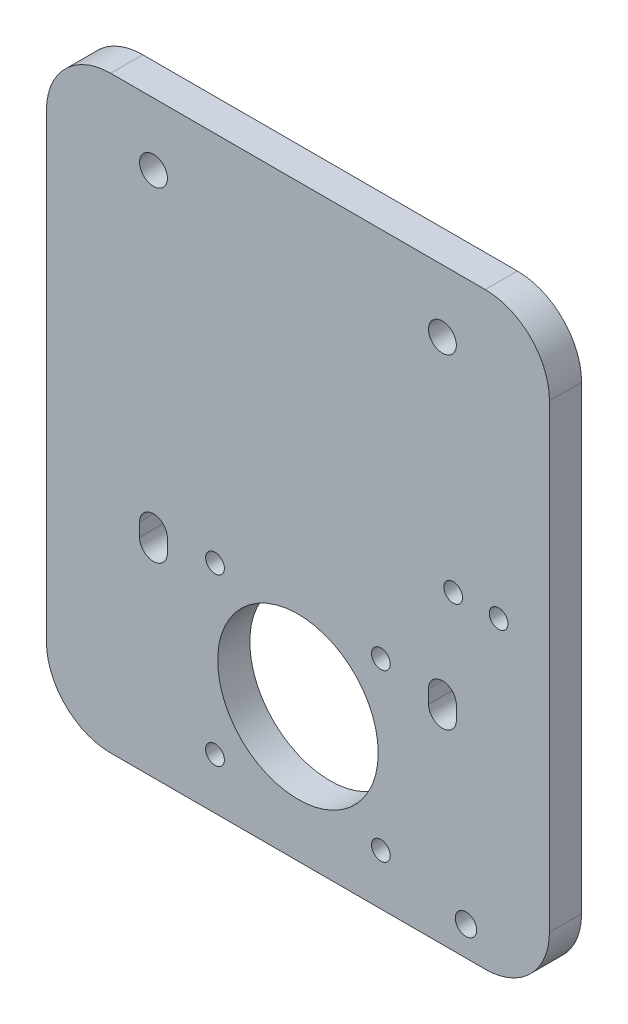
SolidWorks part; units mm, degrees
material "Acrylic (Medium-high impact)"
ref_plane "Спереди" through (0, 0, 0) normal (0, 0, 1) x (1, 0, 0)
ref_plane "Сверху" through (0, 0, 0) normal (0, 1, 0) x (1, 0, 0)
ref_plane "Справа" through (0, 0, 0) normal (1, 0, 0) x (0, 0, -1)
sketch "Model" plane through (0, 0, 0) normal (0, 0, 1) x (1, 0, 0)
  line L4 (-22.7195, 98.3) -> (-31.6357, 98.3) construction
  line L5 (-27, 102.2644) -> (-27, 93.0751) construction
  line L24 (-27, 44.8397) -> (-27, 32.6753) construction
  line L25 (-29.6, 40.1) -> (-29.6, 37.6)
  line L26 (-24.4, 37.6) -> (-24.4, 40.1)
  line L27 (-24.4, 40.1) -> (-24.4, 37.6)
  line L28 (-29.6, 37.6) -> (-29.6, 40.1)
  line L156 (-18.8648, 25) -> (20.0371, 25) construction
  line L157 (13.2088, 9.5) -> (17.9881, 9.5) construction
  line L158 (15.5, 11.4003) -> (15.5, 7.7373) construction
  line L159 (27, 44.8397) -> (27, 32.6753) construction
  line L160 (47, 98) -> (47, 12)
  line L165 (27, 102.2644) -> (27, 93.0751) construction
  line L166 (22.7195, 98.3) -> (31.6357, 98.3) construction
  line L167 (35, 0) -> (-35, 0)
  line L171 (15.5, 38.5997) -> (15.5, 42.2627) construction
  line L172 (13.2088, 40.5) -> (17.9881, 40.5) construction
  line L173 (-13.2088, 40.5) -> (-17.9881, 40.5) construction
  line L174 (-47, 12) -> (-47, 98)
  line L175 (-15.5, 38.5997) -> (-15.5, 42.2627) construction
  line L176 (-15.5, 11.4003) -> (-15.5, 7.7373) construction
  line L177 (-13.2088, 9.5) -> (-17.9881, 9.5) construction
  line L181 (-35, 110) -> (35, 110)
  line L955 (29.6, 37.6) -> (29.6, 40.1)
  line L968 (24.4, 40.1) -> (24.4, 37.6)
  line L1360 (24.4, 37.6) -> (24.4, 40.1)
  line L1373 (29.6, 40.1) -> (29.6, 37.6)
  line L1604 (0, -6.1891) -> (0, 116.9068) construction
  arc A0 (35, 110) -> (47, 98) centre (35, 98) cw
  arc A1 (47, 12) -> (35, 0) centre (35, 12) cw
  arc A2 (-47, 12) -> (-35, 0) centre (-35, 12) ccw
  arc A3 (-47, 98) -> (-35, 110) centre (-35, 98) cw
  circle A4 centre (15.5, 9.5) radius 1.75
  circle A5 centre (15.5, 40.5) radius 1.75
  circle A6 centre (-15.5, 40.5) radius 1.75
  circle A7 centre (-15.5, 9.5) radius 1.75
  circle A8 centre (0, 25) radius 15
  arc A9 (24.4, 40.1) -> (29.6, 40.1) centre (27, 40.1) cw
  arc A10 (24.4, 37.6) -> (29.6, 37.6) centre (27, 37.6) ccw
  circle A19 centre (27, 98.3) radius 2.6
  circle A22 centre (-27, 98.3) radius 2.6
  arc A29 (-24.4, 37.6) -> (-29.6, 37.6) centre (-27, 37.6) cw
  arc A30 (-24.4, 40.1) -> (-29.6, 40.1) centre (-27, 40.1) ccw
  dimension "D1" = 12
  dimension "D11" = 3.5
  dimension "D12" = 30
  dimension "D15" = 2.6
  dimension "D16" = 2.6
  dimension "D38" = 5.2
  dimension "D2" = 70
  dimension "D3" = 110
  dimension "D4" = 25
  dimension "D5" = 15.5
  dimension "D6" = 15.5
  dimension "D7" = 20
  dimension "D13" = 5.2
  dimension "D14" = 2.5
  dimension "D17" = 12.6
  dimension "D36" = 58.2
  dimension "D37" = 27
extrude "Base" add sketch "Model" along normal blind 6
sketch "Sketch1" plane through (0, 0, 0) normal (0, 0, -1) x (-1, 0, 0)
  line L1 (-35, 0) -> (35, 0) construction
  line L3 (-47, 98) -> (-47, 12) construction
  circle A0 centre (-29, 58) radius 1.75
  circle A1 centre (-37.5, 58) radius 1.75
  dimension "D1" = 3.5
  dimension "D3" = 9.5
  dimension "D4" = 8.5
  dimension "D5" = 58
extrude "CableMount" cut sketch "Sketch1" against normal blind 10
sketch "Sketch2" plane through (0, 0, 6) normal (0, 0, 1) x (1, 0, 0)
  circle A0 centre (31.3948, 5.5057) radius 2
  dimension "D1" = 4
extrude "Cut-Extrude1" cut sketch "Sketch2" against normal through all
